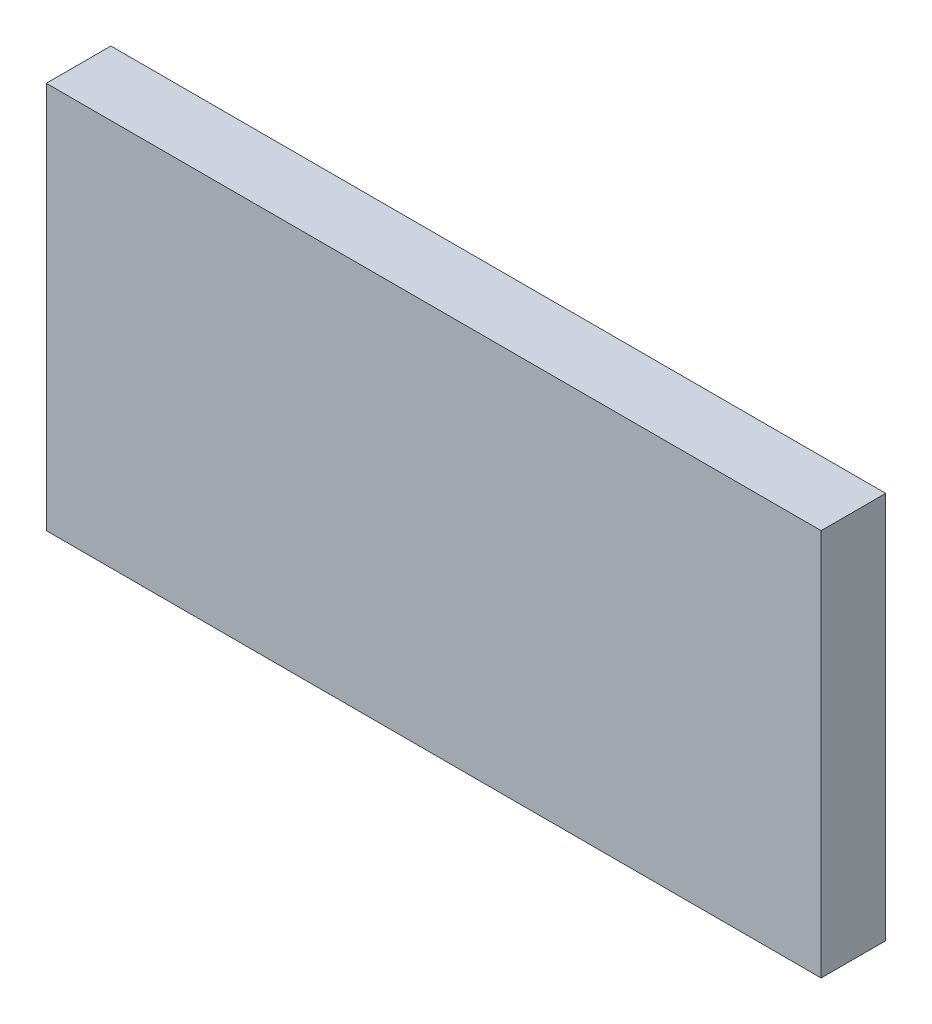
SolidWorks part; units mm, degrees
material "소나무"
ref_plane "정면" through (0, 0, 0) normal (0, 0, 1) x (1, 0, 0)
ref_plane "윗면" through (0, 0, 0) normal (0, 1, 0) x (1, 0, 0)
ref_plane "우측면" through (0, 0, 0) normal (1, 0, 0) x (0, 0, -1)
sketch "스케치1" plane through (0, 0, 0) normal (0, 0, 1) x (1, 0, 0)
  line L1 (-60, 30) -> (60, 30)
  line L2 (-60, 30) -> (-60, -30)
  line L3 (-60, -30) -> (60, -30)
  line L4 (60, 30) -> (60, -30)
  line L5 (-60, 30) -> (60, -30) construction
  line L6 (-60, -30) -> (60, 30) construction
  point P0 (0, 0)
  dimension "D1" = 120
  dimension "D2" = 60
extrude "보스-돌출1" add sketch "스케치1" along normal blind 10
